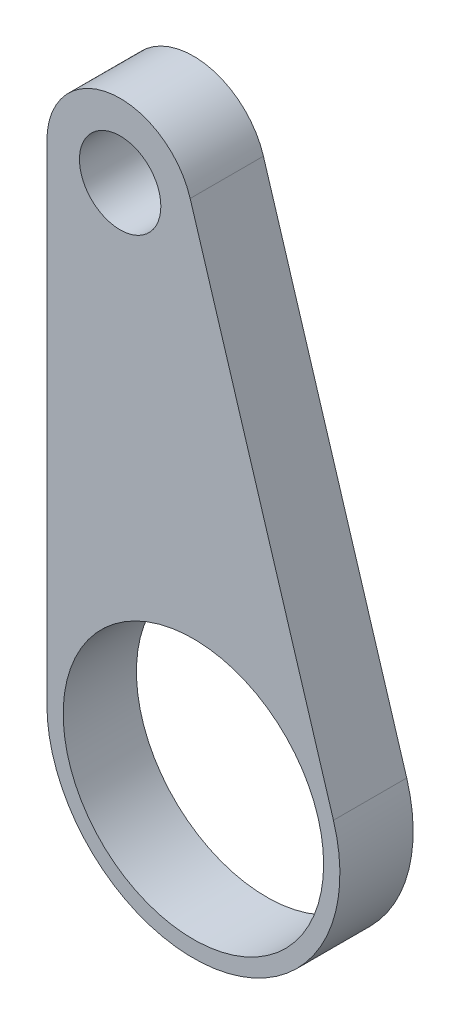
SolidWorks part; units mm, degrees
ref_plane "정면" through (0, 0, 0) normal (0, 0, 1) x (1, 0, 0)
ref_plane "윗면" through (0, 0, 0) normal (0, 1, 0) x (1, 0, 0)
ref_plane "우측면" through (0, 0, 0) normal (1, 0, 0) x (0, 0, -1)
sketch "스케치1" plane through (0, 0, 0) normal (0, 0, 1) x (1, 0, 0)
  line L0 (-9, 0) -> (-9, 30)
  line L1 (8.6039, 2.6406) -> (-0.198, 31.3203)
  circle A0 centre (0, 0) radius 8
  circle A1 centre (0, 0) radius 9
  arc A2 (-9, 30) -> (-0.198, 31.3203) centre (-4.5, 30) cw
  circle A3 centre (-4.5, 30) radius 2.5
  dimension "D1" = 16
  dimension "D2" = 18
  dimension "D3" = 4.5
  dimension "D5" = 5
  dimension "D4" = 30
extrude "보스-돌출1" add sketch "스케치1" along normal blind 4.5 contours A2 L0 A1 L1 A3 | A0
